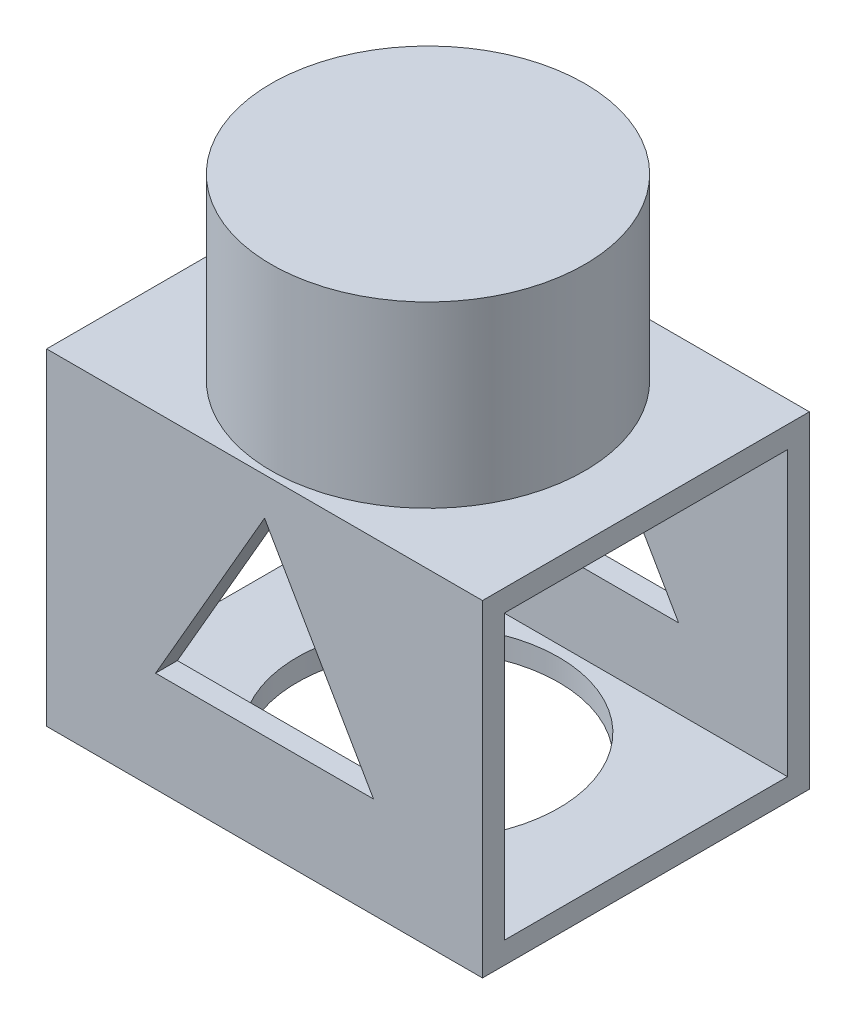
SolidWorks part; units mm, degrees
ref_plane "Front Plane" through (0, 0, 0) normal (0, 0, 1) x (1, 0, 0)
ref_plane "Top Plane" through (0, 0, 0) normal (0, 1, 0) x (1, 0, 0)
ref_plane "Right Plane" through (0, 0, 0) normal (1, 0, 0) x (0, 0, -1)
sketch "Sketch1" plane through (0, 0, 0) normal (0, 1, 0) x (1, 0, 0)
  line L1 (100, -75) -> (-100, -75)
  line L2 (100, -75) -> (100, 75)
  line L3 (100, 75) -> (-100, 75)
  line L4 (-100, -75) -> (-100, 75)
  line L5 (100, -75) -> (-100, 75) construction
  line L6 (100, 75) -> (-100, -75) construction
  point P0 (0, 0)
  dimension "D1" = 150
  dimension "D2" = 200
extrude "Boss-Extrude1" add sketch "Sketch1" along normal blind 150
sketch "Sketch2" plane through (0, 0, 75) normal (0, 0, 1) x (1, 0, 0)
  line L0 (0, 0) -> (0, 150) construction
  line L1 (0, 132.735) -> (-50, 46.1325)
  line L2 (-50, 46.1325) -> (50, 46.1325)
  line L3 (50, 46.1325) -> (0, 132.735)
  line L4 (-100, 150) -> (100, 150) construction
  circle A0 centre (0, 75) radius 28.8675 construction
  dimension "D1" = 100
extrude "Cut-Extrude1" cut sketch "Sketch2" against normal through all
sketch "Sketch3" plane through (100, 0, 0) normal (1, 0, 0) x (0, 0, -1)
  line L0 (0, 150) -> (0, 0) construction
  line L1 (65, 10) -> (-65, 10)
  line L2 (65, 10) -> (65, 140)
  line L3 (65, 140) -> (-65, 140)
  line L4 (-65, 10) -> (-65, 140)
  line L5 (65, 10) -> (-65, 140) construction
  line L6 (65, 140) -> (-65, 10) construction
  line L7 (-75, 150) -> (75, 150) construction
  point P0 (0, 75)
  dimension "D1" = 10
extrude "Cut-Extrude2" cut sketch "Sketch3" against normal through all
sketch "Sketch4" plane through (0, 150, 0) normal (0, 1, 0) x (1, 0, 0)
  circle A0 centre (0, 0) radius 60
  dimension "D1" = 120
extrude "Cut-Extrude3" cut sketch "Sketch4" against normal through all
sketch "Sketch5" plane through (0, 150, 0) normal (0, 1, 0) x (1, 0, 0)
  circle A0 centre (0, 0) radius 71.9339
extrude "Boss-Extrude2" add sketch "Sketch5" along normal blind 82
